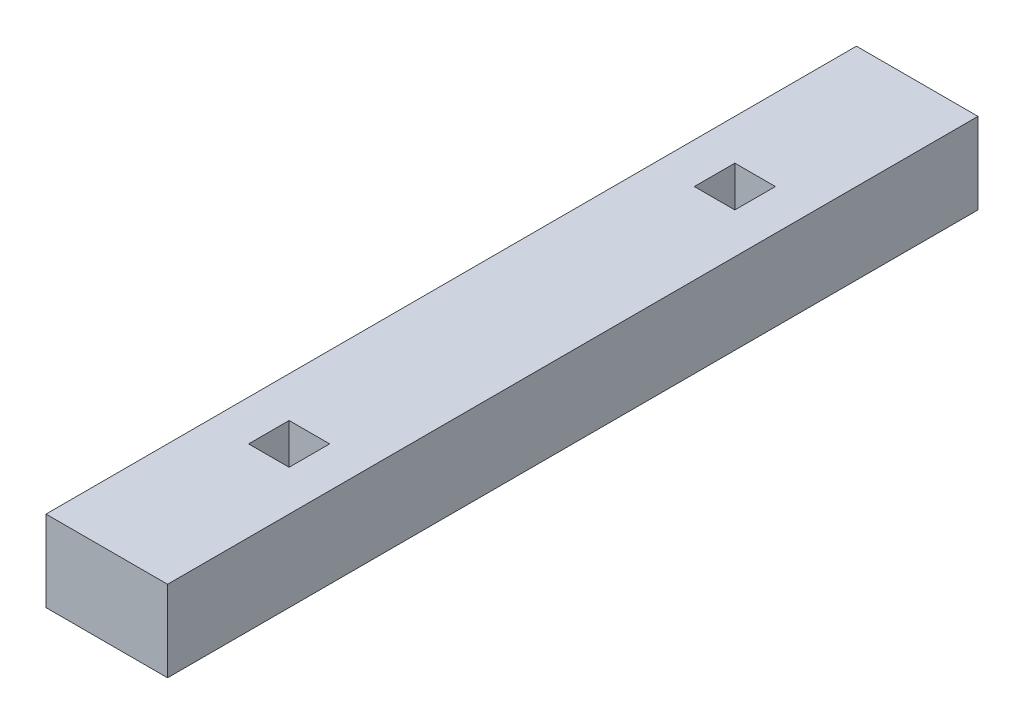
SolidWorks part; units mm, degrees
ref_plane "Front Plane" through (0, 0, 0) normal (0, 0, 1) x (1, 0, 0)
ref_plane "Top Plane" through (0, 0, 0) normal (0, 1, 0) x (1, 0, 0)
ref_plane "Right Plane" through (0, 0, 0) normal (1, 0, 0) x (0, 0, -1)
sketch "Sketch1" plane through (0, 0, 0) normal (0, 1, 0) x (1, 0, 0)
  line L0 (0, 95) -> (0, -105) construction
  line L1 (-15, 95) -> (15, 95)
  line L2 (-15, 95) -> (-15, -105)
  line L3 (-15, -105) -> (15, -105)
  line L4 (15, 95) -> (15, -105)
  line L5 (-5, 55) -> (5, 55)
  line L6 (-5, 55) -> (-5, 45)
  line L7 (-5, 45) -> (5, 45)
  line L8 (5, 55) -> (5, 45)
  line L9 (15, -5) -> (-15, -5) construction
  line L10 (-5, -65) -> (-5, -55)
  line L11 (-5, -55) -> (5, -55)
  line L12 (5, -65) -> (5, -55)
  line L13 (-5, -65) -> (5, -65)
  point P9 (0, 55)
  point P10 (0, 95)
  dimension "D3" = 10
  dimension "D5" = 100
  dimension "D4" = 10
  dimension "D1" = 30
  dimension "D2" = 200
extrude "Boss-Extrude1" add sketch "Sketch1" along normal blind 20
